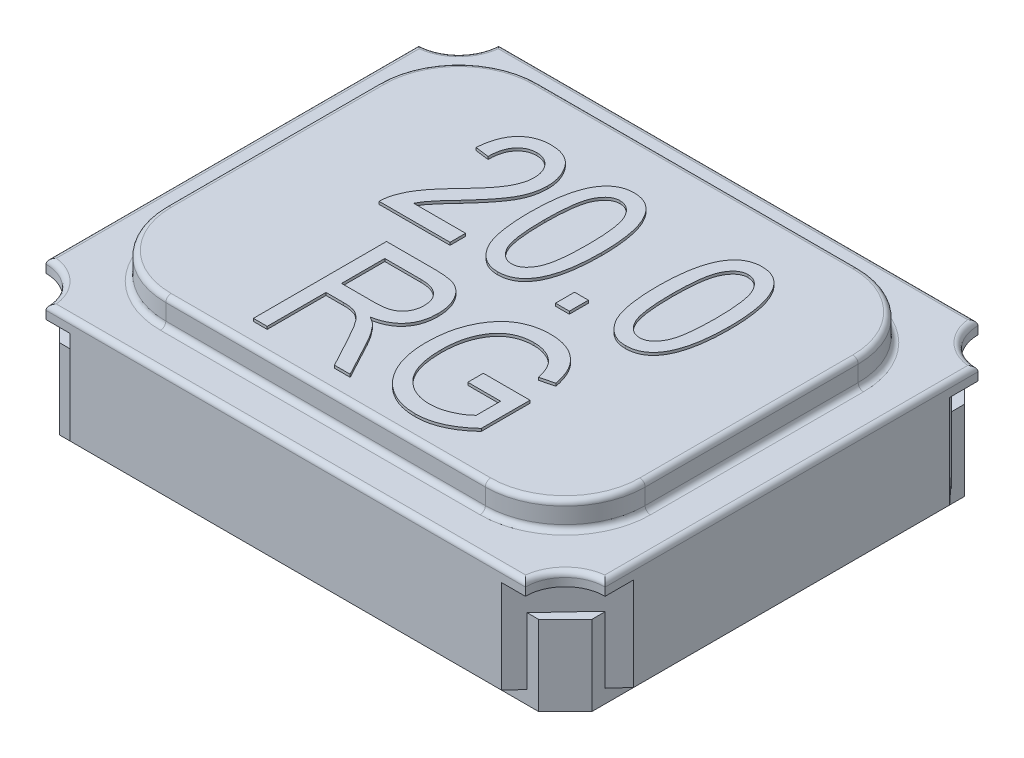
SolidWorks part; units mm, degrees
ref_plane "Спереди" through (0, 0, 0) normal (0, 0, 1) x (1, 0, 0)
ref_plane "Сверху" through (0, 0, 0) normal (0, 1, 0) x (1, 0, 0)
ref_plane "Справа" through (0, 0, 0) normal (1, 0, 0) x (0, 0, -1)
sketch "Эскиз2" plane through (0, 0, 0) normal (0, 1, 0) x (1, 0, 0)
  line L0 (0, 2.0584) -> (0, -2.2706) construction
  line L1 (1, 0.25) -> (0.35, 0.25) construction
  line L2 (1, -0.8) -> (-1, -0.8) construction
  line L3 (1, -0.8) -> (1, 0.8) construction
  line L4 (1, 0.8) -> (-0.9, 0.8) construction
  line L5 (-1, -0.8) -> (-1, 0.7) construction
  line L6 (1, -0.8) -> (-1, 0.8) construction
  line L7 (1, 0.8) -> (-1, -0.8) construction
  line L8 (-1, 0.8) -> (-0.35, 0.8) construction
  line L9 (-1, 0.8) -> (-1, 0.25) construction
  line L10 (-1, 0.25) -> (-0.35, 0.25) construction
  line L11 (-0.35, 0.8) -> (-0.35, 0.25) construction
  line L12 (-1, 0.8) -> (-0.35, 0.25) construction
  line L13 (2.9957, 0) -> (-3.2489, 0) construction
  line L14 (-1, 0.25) -> (-0.35, 0.8) construction
  line L15 (0.35, 0.8) -> (0.35, 0.25) construction
  line L16 (1, 0.8) -> (0.35, 0.8) construction
  line L17 (1, 0.8) -> (1, 0.25) construction
  line L18 (1, 0.25) -> (0.35, 0.8) construction
  line L19 (1, 0.8) -> (0.35, 0.25) construction
  line L20 (1, -0.8) -> (0.35, -0.25) construction
  line L21 (1, -0.25) -> (0.35, -0.8) construction
  line L22 (1, -0.8) -> (1, -0.25) construction
  line L23 (1, -0.8) -> (0.35, -0.8) construction
  line L24 (0.35, -0.8) -> (0.35, -0.25) construction
  line L25 (-1, -0.25) -> (-0.35, -0.8) construction
  line L26 (-1, -0.8) -> (-0.35, -0.25) construction
  line L27 (-0.35, -0.8) -> (-0.35, -0.25) construction
  line L28 (-1, -0.25) -> (-0.35, -0.25) construction
  line L29 (-1, -0.8) -> (-1, -0.25) construction
  line L30 (-1, -0.8) -> (-0.35, -0.8) construction
  line L31 (1, -0.25) -> (0.35, -0.25) construction
  line L32 (-0.9, 0.8) -> (-1, 0.7) construction
  line L33 (-1, 0.25) -> (-0.35, 0.25)
  line L34 (-0.35, 0.25) -> (-0.35, 0.8)
  line L35 (-0.35, 0.8) -> (-0.9, 0.8)
  line L36 (-0.9, 0.8) -> (-1, 0.7)
  line L37 (-1, 0.7) -> (-1, 0.25)
  line L38 (0.35, 0.25) -> (0.35, 0.8)
  line L39 (1, 0.25) -> (0.35, 0.25)
  line L40 (1, 0.7) -> (1, 0.25)
  line L41 (0.9, 0.8) -> (1, 0.7)
  line L42 (0.35, 0.8) -> (0.9, 0.8)
  line L43 (-1, -0.7) -> (-1, -0.25)
  line L44 (-0.9, -0.8) -> (-1, -0.7)
  line L45 (-0.35, -0.8) -> (-0.9, -0.8)
  line L46 (1, -0.25) -> (0.35, -0.25)
  line L47 (1, -0.7) -> (1, -0.25)
  line L48 (0.9, -0.8) -> (1, -0.7)
  line L49 (0.35, -0.8) -> (0.9, -0.8)
  line L50 (0.35, -0.25) -> (0.35, -0.8)
  line L51 (-1, -0.25) -> (-0.484, -0.25)
  line L52 (-0.484, -0.25) -> (-0.35, -0.3634)
  line L53 (-0.35, -0.3634) -> (-0.35, -0.8)
  point P2 (0, 0)
  point P7 (-0.675, 0.525)
  point P19 (0.675, 0.525)
  point P28 (0.675, -0.525)
  point P29 (-0.675, -0.525)
  dimension "D8" = 45
  dimension "D1" = 1.6
  dimension "D2" = 2
  dimension "D3" = 1.05
  dimension "D4" = 1.35
  dimension "D5" = 0.55
  dimension "D6" = 0.65
  dimension "D7" = 0.1
  dimension "D9" = 0.516
extrude "Вытянуть2" add sketch "Эскиз2" along normal blind 0.05
ref_plane "Плоскость1" through (-0.35, 0.05, 0.8) normal (0, 1, 0) x (-1, 0, 0)
sketch "Эскиз3" plane through (-0.35, 0.05, 0.8) normal (0, 1, 0) x (-1, 0, 0)
  line L0 (0.65, -1.5) -> (0.55, -1.6)
  line L1 (0.55, -1.6) -> (0.5, -1.6)
  line L2 (0, -1.6) -> (0.55, -1.6) construction
  line L3 (0.5, -1.6) -> (0.65, -1.45)
  line L4 (0.65, -1.5) -> (0.65, -1.05) construction
  line L5 (1.1032, -0.8) -> (-1.8964, -0.8) construction
  line L6 (-0.35, 0.2875) -> (-0.35, -2.7218) construction
  line L7 (0.65, -1.45) -> (0.65, -1.5)
  line L8 (-1.35, -1.45) -> (-1.35, -1.5)
  line L9 (-1.2, -1.6) -> (-1.35, -1.45)
  line L10 (-1.25, -1.6) -> (-1.2, -1.6)
  line L11 (-1.35, -1.5) -> (-1.25, -1.6)
  line L12 (-1.35, -0.1) -> (-1.25, 0)
  line L13 (-1.25, 0) -> (-1.2, 0)
  line L14 (-1.2, 0) -> (-1.35, -0.15)
  line L15 (-1.35, -0.15) -> (-1.35, -0.1)
  line L16 (0.65, -0.15) -> (0.65, -0.1)
  line L17 (0.5, 0) -> (0.65, -0.15)
  line L18 (0.55, 0) -> (0.5, 0)
  line L19 (0.65, -0.1) -> (0.55, 0)
  dimension "D1" = 0.05
extrude "Вытянуть4" add sketch "Эскиз3" along normal blind 0.25
sketch "Эскиз4" plane through (-0.35, 0.05, 0.8) normal (0, 1, 0) x (-1, 0, 0)
  line L0 (0.6064, -1.4936) -> (0.2699, -1.8531) construction
  line L3 (0.65, -1.45) -> (0.5, -1.6) construction
  line L5 (-0.35, -1.8558) -> (-0.35, 0.3574) construction
  line L6 (0.65, -1.45) -> (0.5, -1.6) construction
  line L8 (0.6064, -0.1064) -> (0.2699, 0.2531) construction
  line L9 (-1.3064, -0.1064) -> (-0.9699, 0.2531) construction
  line L10 (-1.3064, -1.4936) -> (-0.9699, -1.8531) construction
  line L13 (0.46, -1.65) -> (-1.16, -1.65)
  line L14 (-1.4, 0.05) -> (0.7, 0.05) construction
  line L15 (1.0658, -0.8) -> (-2.5223, -0.8) construction
  line L16 (-1.4, 0.05) -> (-1.4, -1.65) construction
  line L17 (-1.4, -1.65) -> (0.7, -1.65) construction
  line L18 (0.7, 0.05) -> (0.7, -1.65) construction
  line L19 (-1.16, -1.65) -> (-1.4, -1.3936)
  line L20 (-1.4, 0.05) -> (0.7, -1.65) construction
  line L21 (-1.4, -1.65) -> (0.7, 0.05) construction
  line L22 (-1.4, -1.3936) -> (-1.4, -0.2064)
  line L23 (-1.4, -0.2064) -> (-1.16, 0.05)
  line L24 (-1.16, 0.05) -> (0.46, 0.05)
  line L25 (0.46, 0.05) -> (0.7, -0.2064)
  line L26 (0.7, -0.2064) -> (0.7, -1.3936)
  line L27 (0.7, -1.3936) -> (0.46, -1.65)
  point P16 (-0.35, -0.8)
  dimension "D2" = 2.1
  dimension "D1" = 1.7
  dimension "D3" = 0.24
extrude "Вытянуть6" add sketch "Эскиз4" along normal blind 0.35
ref_plane "Плоскость2" through (0, 0.4, 0.85) normal (0, 1, 0) x (-1, 0, 0)
sketch "Эскиз5" plane through (0, 0.4, 0.85) normal (0, 1, 0) x (-1, 0, 0)
  line L0 (-1.179, -0.85) -> (1.1884, -0.85) construction
  line L2 (0.9, -1.7) -> (-0.9, -1.7)
  line L3 (-1.05, 0) -> (1.05, 0) construction
  line L4 (-1.05, 0) -> (-1.05, -1.7) construction
  line L5 (-1.05, -1.7) -> (1.05, -1.7) construction
  line L6 (1.05, 0) -> (1.05, -1.7) construction
  line L7 (0, -2.1539) -> (0, 0.2767) construction
  line L8 (-1.05, 0) -> (1.05, -1.7) construction
  line L9 (-1.05, -1.7) -> (1.05, 0) construction
  line L10 (-1.05, -1.55) -> (-1.05, -0.15)
  line L12 (-0.9, 0) -> (0.9, 0)
  line L13 (1.05, -0.15) -> (1.05, -1.55)
  arc A0 (1.05, -0.15) -> (0.9, 0) centre (1.05, 0) cw
  arc A1 (-1.05, -0.15) -> (-0.9, 0) centre (-1.05, 0) ccw
  arc A2 (-1.05, -1.55) -> (-0.9, -1.7) centre (-1.05, -1.7) cw
  arc A3 (1.05, -1.55) -> (0.9, -1.7) centre (1.05, -1.7) ccw
  point P2 (0, -0.85)
  dimension "D3" = 0.15
  dimension "D1" = 2.1
  dimension "D2" = 1.7
extrude "Вытянуть9" add sketch "Эскиз5" along normal blind 0.05
sketch "Эскиз6" plane through (0, 0.45, 0) normal (0, 1, 0) x (1, 0, 0)
  line L1 (0.9, -0.7) -> (-0.9, -0.7)
  line L2 (0.9, -0.7) -> (0.9, 0.7)
  line L3 (0.9, 0.7) -> (-0.9, 0.7)
  line L4 (-0.9, -0.7) -> (-0.9, 0.7)
  line L5 (0.9, -0.7) -> (-0.9, 0.7) construction
  line L6 (0.9, 0.7) -> (-0.9, -0.7) construction
  point P0 (0, 0)
  dimension "D1" = 1.8
  dimension "D2" = 1.4
extrude "Вытянуть10" add sketch "Эскиз6" along normal blind 0.1
fillet "Скругление2" radius 0.3 4 edges at (0.9, 0.5, -0.7) (0.9, 0.5, 0.7) (-0.9, 0.5, -0.7) (-0.9, 0.5, 0.7)
fillet "Скругление3" radius 0.02 24 edges at (0.8121, 0.45, 0.6121) (0.9, 0.45, 0) (0.8121, 0.45, -0.6121) (0, 0.45, -0.7) (-0.8121, 0.45, -0.6121) (-0.9, 0.45, 0) (-0.8121, 0.45, 0.6121) (0, 0.45, 0.7) (0.8121, 0.55, 0.6121) (0, 0.55, 0.7) (-0.8121, 0.55, 0.6121) (-0.9, 0.55, 0) (-0.8121, 0.55, -0.6121) (0, 0.55, -0.7) (0.8121, 0.55, -0.6121) (0.9, 0.55, 0) (-1.05, 0.45, 0) (-0.9439, 0.45, -0.7439) (0, 0.45, -0.85) (0.9439, 0.45, -0.7439) (1.05, 0.45, 0) (0.9439, 0.45, 0.7439) (0, 0.45, 0.85) (-0.9439, 0.45, 0.7439)
sketch "Эскиз7" plane through (0, 0.55, 0) normal (0, 1, 0) x (-1, 0, 0)
  line L0 (0.5249, 0) -> (-0.7346, 0) construction
  line L1 (0.4, 0.6167) -> (-0.8354, 0.6167) construction
  line L2 (-1.179, 0) -> (1.1884, 0) construction
  text T0 "20.0" font "Arial Narrow" height 0.5
  text T1 "RG" font "Arial Narrow" height 0.5
extrude "Вытянуть11" add sketch "Эскиз7" along normal blind 0.01
